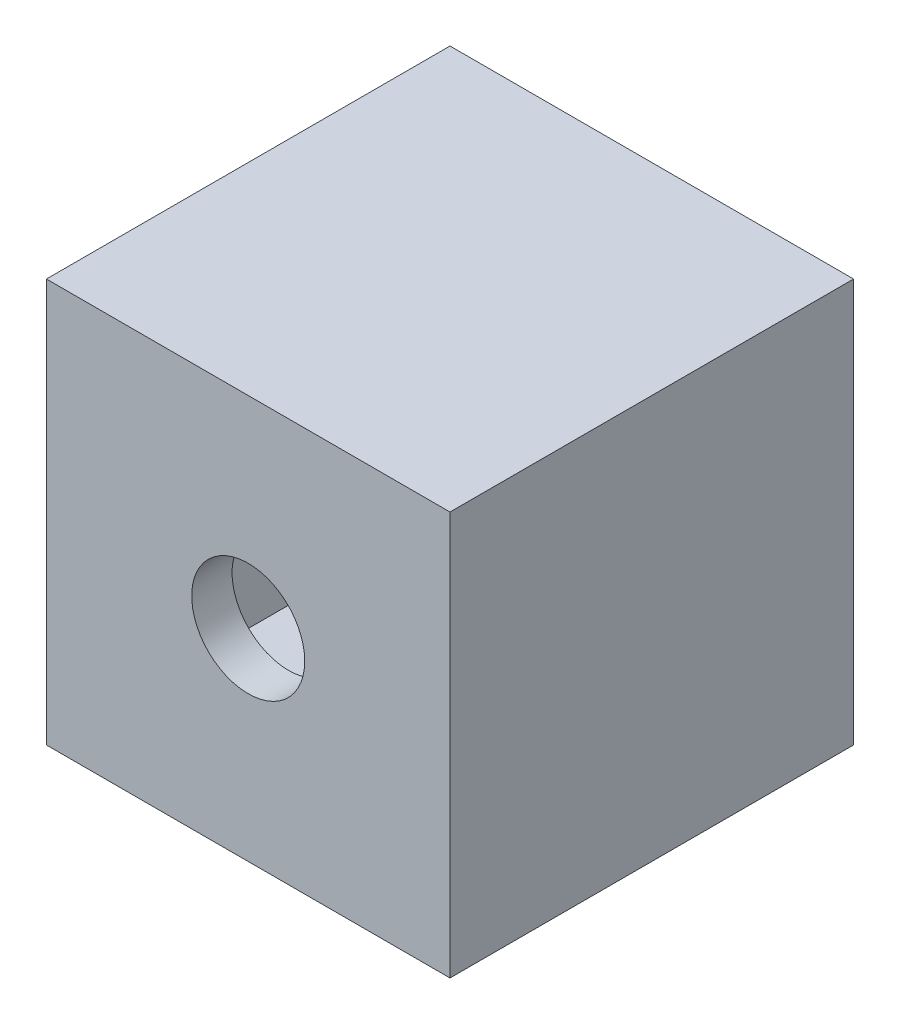
SolidWorks part; units mm, degrees
material "Beech"
ref_plane "Front Plane" through (0, 0, 0) normal (0, 0, 1) x (1, 0, 0)
ref_plane "Top Plane" through (0, 0, 0) normal (0, 1, 0) x (1, 0, 0)
ref_plane "Right Plane" through (0, 0, 0) normal (1, 0, 0) x (0, 0, -1)
sketch "Sketch5" plane through (0, 0, 0) normal (0, 0, 1) x (1, 0, 0)
  line L1 (-100, -100) -> (100, -100)
  line L2 (-100, -100) -> (-100, 100)
  line L3 (-100, 100) -> (100, 100)
  line L4 (100, -100) -> (100, 100)
  line L5 (-100, -100) -> (100, 100) construction
  line L6 (-100, 100) -> (100, -100) construction
  point P0 (0, 0)
  dimension "D1" = 200
  dimension "D2" = 200
extrude "Boss-Extrude2" add sketch "Sketch5" along normal blind 200
shell "Shell2" thickness 20
sketch "Sketch6" plane through (0, 0, 200) normal (0, 0, 1) x (1, 0, 0)
  circle A0 centre (0, 0) radius 28
  dimension "D1" = 56
extrude "Cut-Extrude2" cut sketch "Sketch6" against normal blind 51.6
